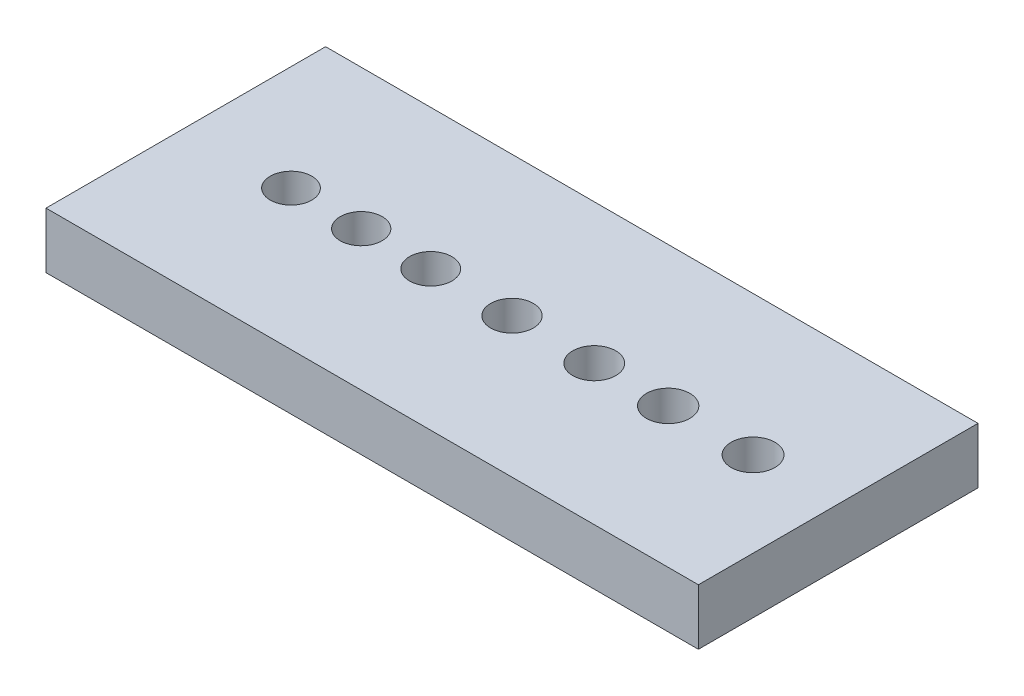
SolidWorks part; units mm, degrees
ref_plane "Alzado" through (0, 0, 0) normal (0, 0, 1) x (1, 0, 0)
ref_plane "Planta" through (0, 0, 0) normal (0, 1, 0) x (1, 0, 0)
ref_plane "Vista lateral" through (0, 0, 0) normal (1, 0, 0) x (0, 0, -1)
sketch "Croquis1" plane through (0, 0, 0) normal (0, 1, 0) x (1, 0, 0)
  line L0 (-11.8545, 0) -> (12.9314, 0) construction
  line L2 (-17.5, 7.5) -> (17.5, 7.5)
  line L3 (-17.5, 7.5) -> (-17.5, -7.5)
  line L4 (-17.5, -7.5) -> (17.5, -7.5)
  line L5 (17.5, 7.5) -> (17.5, -7.5)
  circle A0 centre (-11.8545, 0) radius 1.115
  circle A1 centre (-8.0891, 0) radius 1.125
  circle A2 centre (-4.3602, 0) radius 1.135
  circle A3 centre (0, 0) radius 1.145
  circle A4 centre (4.4135, 0) radius 1.155
  circle A5 centre (8.3786, 0) radius 1.165
  circle A6 centre (12.9314, 0) radius 1.175
  dimension "D1" = 2.23
  dimension "D2" = 2.25
  dimension "D3" = 2.27
  dimension "D4" = 2.29
  dimension "D5" = 2.31
  dimension "D6" = 2.33
  dimension "D7" = 2.35
  dimension "D8" = 24.7859
  dimension "D9" = 15
  dimension "D10" = 7.5
  dimension "D11" = 35
  dimension "D12" = 17.5
extrude "Saliente-Extruir1" add sketch "Croquis1" along normal blind 3
